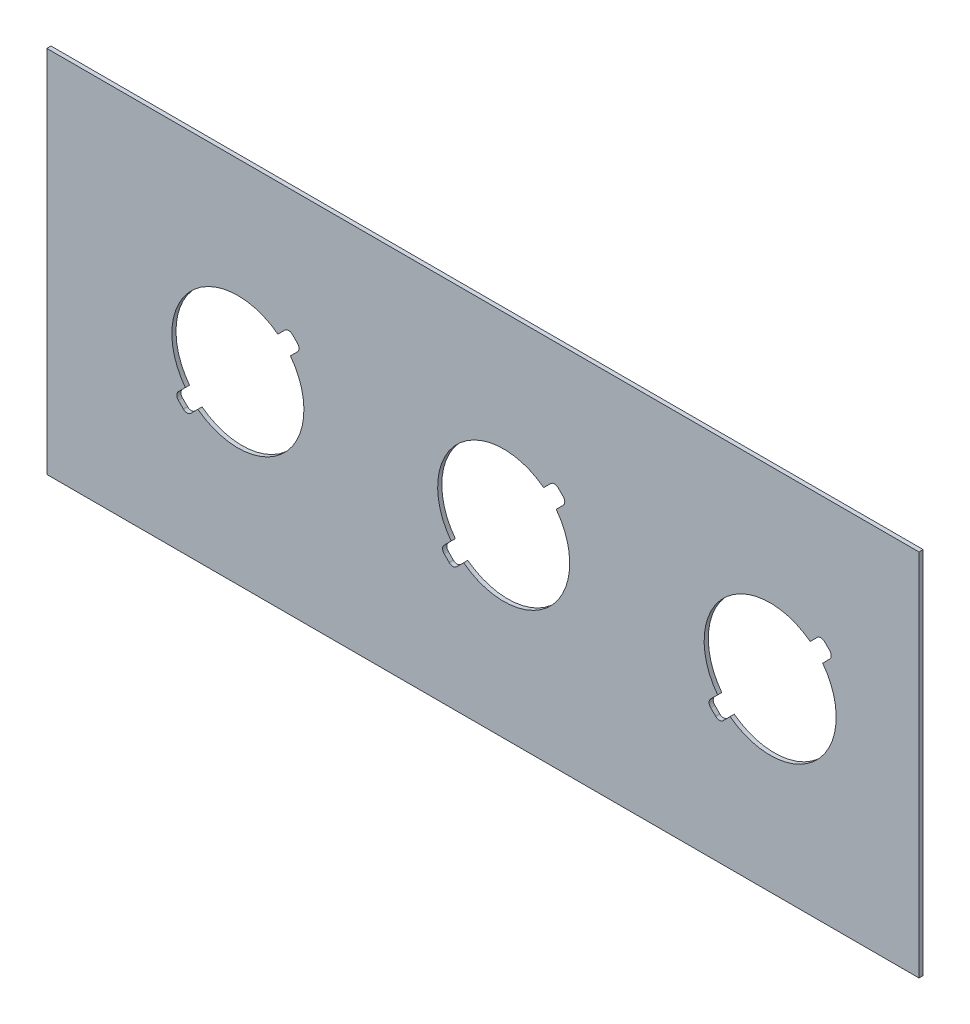
SolidWorks part; units mm, degrees
ref_plane "Front Plane" through (0, 0, 0) normal (0, 0, 1) x (1, 0, 0)
ref_plane "Top Plane" through (0, 0, 0) normal (0, 1, 0) x (1, 0, 0)
ref_plane "Right Plane" through (0, 0, 0) normal (1, 0, 0) x (0, 0, -1)
sketch "Sketch1" plane through (0, 0, 0) normal (0, 0, 1) x (1, 0, 0)
  line L1 (-165.1, -69.85) -> (165.1, -69.85)
  line L2 (-165.1, -69.85) -> (-165.1, 69.85)
  line L3 (-165.1, 69.85) -> (165.1, 69.85)
  line L4 (165.1, -69.85) -> (165.1, 69.85)
  line L5 (-165.1, -69.85) -> (165.1, 69.85) construction
  line L6 (-165.1, 69.85) -> (165.1, -69.85) construction
  point P0 (0, 0)
  dimension "D1" = 330.2
  dimension "D2" = 139.7
extrude "Boss-Extrude1" add sketch "Sketch1" along normal blind 1.5748
sketch "Sketch6" plane through (0, 0, 1.5748) normal (0, 0, 1) x (1, 0, 0)
  circle A10 centre (108.75, 0) radius 25
  circle A11 centre (7.861, 0) radius 25
  circle A12 centre (-92.774, 0) radius 25
  dimension "D1" = 50
extrude "Cut-Extrude3" cut sketch "Sketch6" against normal through all
sketch "Sketch8" plane through (0, 0, 1.5748) normal (0, 0, 1) x (1, 0, 0)
  line L0 (88.1205, -22.5387) -> (86.2113, -20.6295) construction
  line L1 (93.6006, -19.887) -> (90.9489, -22.5387) construction
  line L2 (86.2113, -17.8011) -> (88.863, -15.1494) construction
  line L3 (88.1205, -22.5387) -> (86.2113, -20.6295)
  line L4 (93.6006, -19.887) -> (90.9489, -22.5387)
  line L5 (86.2113, -17.8011) -> (88.863, -15.1494)
  line L6 (123.8994, 19.887) -> (126.5511, 22.5387) construction
  line L7 (131.2887, 17.8011) -> (128.637, 15.1494) construction
  line L8 (129.3795, 22.5387) -> (131.2887, 20.6295) construction
  line L9 (131.2887, 17.8011) -> (128.637, 15.1494)
  line L10 (129.3795, 22.5387) -> (131.2887, 20.6295)
  line L11 (123.8994, 19.887) -> (126.5511, 22.5387)
  line L12 (30.3997, 17.8011) -> (27.748, 15.1494) construction
  line L13 (28.4905, 22.5387) -> (30.3997, 20.6295) construction
  line L14 (23.0104, 19.887) -> (25.6621, 22.5387) construction
  line L15 (-7.2884, -19.887) -> (-9.9401, -22.5387) construction
  line L16 (-12.7685, -22.5387) -> (-14.6777, -20.6295) construction
  line L17 (-14.6777, -17.8011) -> (-12.026, -15.1494) construction
  line L18 (30.3997, 17.8011) -> (27.748, 15.1494)
  line L19 (28.4905, 22.5387) -> (30.3997, 20.6295)
  line L20 (23.0104, 19.887) -> (25.6621, 22.5387)
  line L21 (-7.2884, -19.887) -> (-9.9401, -22.5387)
  line L22 (-12.7685, -22.5387) -> (-14.6777, -20.6295)
  line L23 (-14.6777, -17.8011) -> (-12.026, -15.1494)
  line L24 (-115.3127, -17.8011) -> (-112.661, -15.1494) construction
  line L25 (-107.9234, -19.887) -> (-110.5751, -22.5387) construction
  line L26 (-113.4035, -22.5387) -> (-115.3127, -20.6295) construction
  line L27 (-115.3127, -17.8011) -> (-112.661, -15.1494)
  line L28 (-107.9234, -19.887) -> (-110.5751, -22.5387)
  line L29 (-113.4035, -22.5387) -> (-115.3127, -20.6295)
  line L30 (-70.2353, 17.8011) -> (-72.887, 15.1494) construction
  line L31 (-72.1445, 22.5387) -> (-70.2353, 20.6295) construction
  line L32 (-77.6246, 19.887) -> (-74.9729, 22.5387) construction
  line L33 (-70.2353, 17.8011) -> (-72.887, 15.1494)
  line L34 (-72.1445, 22.5387) -> (-70.2353, 20.6295)
  line L35 (-77.6246, 19.887) -> (-74.9729, 22.5387)
  arc A0 (86.2113, -17.8011) -> (86.2113, -20.6295) centre (87.6255, -19.2153) ccw construction
  arc A1 (88.1205, -22.5387) -> (90.9489, -22.5387) centre (89.5347, -21.1245) ccw construction
  arc A2 (131.2887, 17.8011) -> (131.2887, 20.6295) centre (129.8745, 19.2153) ccw construction
  arc A3 (86.2113, -17.8011) -> (86.2113, -20.6295) centre (87.6255, -19.2153) ccw
  arc A4 (88.1205, -22.5387) -> (90.9489, -22.5387) centre (89.5347, -21.1245) ccw
  arc A6 (129.3795, 22.5387) -> (126.5511, 22.5387) centre (127.9653, 21.1245) ccw construction
  arc A7 (131.2887, 17.8011) -> (131.2887, 20.6295) centre (129.8745, 19.2153) ccw
  arc A8 (129.3795, 22.5387) -> (126.5511, 22.5387) centre (127.9653, 21.1245) ccw
  arc A9 (30.3997, 17.8011) -> (30.3997, 20.6295) centre (28.9855, 19.2153) ccw construction
  arc A10 (28.4905, 22.5387) -> (25.6621, 22.5387) centre (27.0763, 21.1245) ccw construction
  arc A11 (-12.7685, -22.5387) -> (-9.9401, -22.5387) centre (-11.3543, -21.1245) ccw construction
  arc A12 (-14.6777, -17.8011) -> (-14.6777, -20.6295) centre (-13.2635, -19.2153) ccw construction
  arc A13 (30.3997, 17.8011) -> (30.3997, 20.6295) centre (28.9855, 19.2153) ccw
  arc A14 (28.4905, 22.5387) -> (25.6621, 22.5387) centre (27.0763, 21.1245) ccw
  arc A15 (-12.7685, -22.5387) -> (-9.9401, -22.5387) centre (-11.3543, -21.1245) ccw
  arc A16 (-14.6777, -17.8011) -> (-14.6777, -20.6295) centre (-13.2635, -19.2153) ccw
  arc A17 (-115.3127, -17.8011) -> (-115.3127, -20.6295) centre (-113.8985, -19.2153) ccw construction
  arc A18 (-113.4035, -22.5387) -> (-110.5751, -22.5387) centre (-111.9893, -21.1245) ccw construction
  arc A19 (-115.3127, -17.8011) -> (-115.3127, -20.6295) centre (-113.8985, -19.2153) ccw
  arc A20 (-113.4035, -22.5387) -> (-110.5751, -22.5387) centre (-111.9893, -21.1245) ccw
  arc A21 (-70.2353, 17.8011) -> (-70.2353, 20.6295) centre (-71.6495, 19.2153) ccw construction
  arc A22 (-72.1445, 22.5387) -> (-74.9729, 22.5387) centre (-73.5587, 21.1245) ccw construction
  arc A23 (-70.2353, 17.8011) -> (-70.2353, 20.6295) centre (-71.6495, 19.2153) ccw
  arc A24 (-72.1445, 22.5387) -> (-74.9729, 22.5387) centre (-73.5587, 21.1245) ccw
  arc A25 (128.637, 15.1494) -> (123.8994, 19.887) centre (108.75, 0) ccw
  arc A26 (27.748, 15.1494) -> (23.0104, 19.887) centre (7.861, 0) ccw
  arc A27 (-72.887, 15.1494) -> (-77.6246, 19.887) centre (-92.774, 0) ccw
  arc A28 (-112.661, -15.1494) -> (-107.9234, -19.887) centre (-92.774, 0) ccw
  arc A29 (-12.026, -15.1494) -> (-7.2884, -19.887) centre (7.861, 0) ccw
  arc A30 (88.863, -15.1494) -> (93.6006, -19.887) centre (108.75, 0) ccw
extrude "Cut-Extrude4" cut sketch "Sketch8" against normal blind 4
sketch "Sketch9" plane through (0, 0, 1.5748) normal (0, 0, 1) x (1, 0, 0)
  line L0 (108.75, -26.27) -> (108.75, -25)
  line L1 (135.02, -26.27) -> (82.48, -26.27) construction
  line L2 (82.48, 26.27) -> (135.02, 26.27) construction
  line L3 (135.02, 0) -> (133.75, 0)
  line L4 (82.48, -26.27) -> (82.48, 26.27) construction
  line L5 (-18.409, 0) -> (-17.139, 0)
  line L6 (34.131, 26.27) -> (34.131, -26.27) construction
  line L7 (-119.044, 0) -> (-117.774, 0)
  line L8 (-66.504, 26.27) -> (-66.504, -26.27) construction
  line L9 (7.861, 26.27) -> (7.861, 25)
  line L10 (34.131, -26.27) -> (-18.409, -26.27) construction
  line L11 (-92.774, 26.27) -> (-92.774, 25)
  line L12 (-66.504, -26.27) -> (-119.044, -26.27) construction
  line L16 (93.6006, -19.887) -> (90.9489, -22.5387) construction
  line L17 (88.1205, -22.5387) -> (86.2113, -20.6295) construction
  line L18 (86.2113, -17.8011) -> (88.863, -15.1494) construction
  line L19 (131.2887, 17.8011) -> (128.637, 15.1494) construction
  line L20 (129.3795, 22.5387) -> (131.2887, 20.6295) construction
  line L21 (123.8994, 19.887) -> (126.5511, 22.5387) construction
  line L22 (131.2887, 17.8011) -> (128.637, 15.1494)
  line L23 (129.3795, 22.5387) -> (131.2887, 20.6295)
  line L24 (123.8994, 19.887) -> (126.5511, 22.5387)
  line L25 (93.6006, -19.887) -> (90.9489, -22.5387)
  line L26 (88.1205, -22.5387) -> (86.2113, -20.6295)
  line L27 (86.2113, -17.8011) -> (88.863, -15.1494)
  line L28 (83.75, 0) -> (82.48, 0)
  line L29 (135.02, 26.27) -> (108.75, 26.27)
  line L30 (135.02, 26.27) -> (135.02, 0)
  line L31 (108.75, -26.27) -> (82.48, -26.27)
  line L32 (82.48, 0) -> (82.48, -26.27)
  line L34 (-7.2884, -19.887) -> (-9.9401, -22.5387) construction
  line L35 (-12.7685, -22.5387) -> (-14.6777, -20.6295) construction
  line L36 (108.75, 25) -> (108.75, 26.27)
  line L38 (-14.6777, -17.8011) -> (-12.026, -15.1494) construction
  line L39 (-7.2884, -19.887) -> (-9.9401, -22.5387)
  line L40 (-12.7685, -22.5387) -> (-14.6777, -20.6295)
  line L41 (-14.6777, -17.8011) -> (-12.026, -15.1494)
  line L42 (30.3997, 17.8011) -> (27.748, 15.1494) construction
  line L43 (28.4905, 22.5387) -> (30.3997, 20.6295) construction
  line L44 (23.0104, 19.887) -> (25.6621, 22.5387) construction
  line L45 (30.3997, 17.8011) -> (27.748, 15.1494)
  line L46 (28.4905, 22.5387) -> (30.3997, 20.6295)
  line L47 (23.0104, 19.887) -> (25.6621, 22.5387)
  line L48 (-107.9234, -19.887) -> (-110.5751, -22.5387) construction
  line L49 (-113.4035, -22.5387) -> (-115.3127, -20.6295) construction
  line L50 (-115.3127, -17.8011) -> (-112.661, -15.1494) construction
  line L51 (-107.9234, -19.887) -> (-110.5751, -22.5387)
  line L52 (-113.4035, -22.5387) -> (-115.3127, -20.6295)
  line L53 (-115.3127, -17.8011) -> (-112.661, -15.1494)
  line L54 (-77.6246, 19.887) -> (-74.9729, 22.5387) construction
  line L55 (-72.1445, 22.5387) -> (-70.2353, 20.6295) construction
  line L56 (-70.2353, 17.8011) -> (-72.887, 15.1494) construction
  line L57 (-77.6246, 19.887) -> (-74.9729, 22.5387)
  line L58 (-72.1445, 22.5387) -> (-70.2353, 20.6295)
  line L59 (-70.2353, 17.8011) -> (-72.887, 15.1494)
  line L60 (7.861, -25) -> (7.861, -26.27)
  line L61 (34.131, 26.27) -> (7.861, 26.27)
  line L62 (34.131, 26.27) -> (34.131, 0)
  line L63 (7.861, -26.27) -> (-18.409, -26.27)
  line L64 (-18.409, 0) -> (-18.409, -26.27)
  line L66 (-92.774, -25) -> (-92.774, -26.27)
  line L67 (-66.504, 26.27) -> (-92.774, 26.27)
  line L68 (-66.504, 26.27) -> (-66.504, 0)
  line L69 (-92.774, -26.27) -> (-119.044, -26.27)
  line L70 (-119.044, 0) -> (-119.044, -26.27)
  line L72 (-119.044, 26.27) -> (-66.504, 26.27) construction
  line L73 (32.861, 0) -> (34.131, 0)
  line L76 (-67.774, 0) -> (-66.504, 0)
  line L77 (-139.7, -69.85) -> (-139.7, 69.85)
  line L78 (-139.7, -88.9) -> (-139.7, 88.9) construction
  line L79 (-165.1, -69.85) -> (165.1, -69.85) construction
  line L80 (165.1, 69.85) -> (-165.1, 69.85) construction
  line L81 (-139.7, -49.75) -> (-165.1, -49.75)
  line L82 (-150.78, -49.75) -> (226.1, -49.75) construction
  line L83 (-165.1, 69.85) -> (-165.1, -69.85) construction
  line L84 (-139.7, 49.95) -> (-165.1, 49.95)
  line L85 (226.1, 49.95) -> (-150.78, 49.95) construction
  arc A0 (83.75, 0) -> (88.863, -15.1494) centre (108.75, 0) ccw
  arc A1 (32.861, 0) -> (27.748, 15.1494) centre (7.861, 0) ccw
  arc A2 (-67.774, 0) -> (-72.887, 15.1494) centre (-92.774, 0) ccw
  arc A3 (86.2113, -17.8011) -> (86.2113, -20.6295) centre (87.6255, -19.2153) ccw construction
  arc A5 (88.1205, -22.5387) -> (90.9489, -22.5387) centre (89.5347, -21.1245) ccw construction
  arc A6 (131.2887, 17.8011) -> (131.2887, 20.6295) centre (129.8745, 19.2153) ccw construction
  arc A7 (129.3795, 22.5387) -> (126.5511, 22.5387) centre (127.9653, 21.1245) ccw construction
  arc A8 (131.2887, 17.8011) -> (131.2887, 20.6295) centre (129.8745, 19.2153) ccw
  arc A9 (129.3795, 22.5387) -> (126.5511, 22.5387) centre (127.9653, 21.1245) ccw
  arc A10 (88.1205, -22.5387) -> (90.9489, -22.5387) centre (89.5347, -21.1245) ccw
  arc A11 (86.2113, -17.8011) -> (86.2113, -20.6295) centre (87.6255, -19.2153) ccw
  arc A12 (133.75, 0) -> (128.637, 15.1494) centre (108.75, 0) ccw
  arc A13 (93.6006, -19.887) -> (108.75, -25) centre (108.75, 0) ccw
  arc A14 (123.8994, 19.887) -> (108.75, 25) centre (108.75, 0) ccw
  arc A15 (-12.7685, -22.5387) -> (-9.9401, -22.5387) centre (-11.3543, -21.1245) ccw construction
  arc A16 (-14.6777, -17.8011) -> (-14.6777, -20.6295) centre (-13.2635, -19.2153) ccw construction
  arc A17 (-12.7685, -22.5387) -> (-9.9401, -22.5387) centre (-11.3543, -21.1245) ccw
  arc A18 (-14.6777, -17.8011) -> (-14.6777, -20.6295) centre (-13.2635, -19.2153) ccw
  arc A19 (30.3997, 17.8011) -> (30.3997, 20.6295) centre (28.9855, 19.2153) ccw construction
  arc A20 (28.4905, 22.5387) -> (25.6621, 22.5387) centre (27.0763, 21.1245) ccw construction
  arc A21 (30.3997, 17.8011) -> (30.3997, 20.6295) centre (28.9855, 19.2153) ccw
  arc A22 (28.4905, 22.5387) -> (25.6621, 22.5387) centre (27.0763, 21.1245) ccw
  arc A23 (-113.4035, -22.5387) -> (-110.5751, -22.5387) centre (-111.9893, -21.1245) ccw construction
  arc A24 (-115.3127, -17.8011) -> (-115.3127, -20.6295) centre (-113.8985, -19.2153) ccw construction
  arc A25 (-113.4035, -22.5387) -> (-110.5751, -22.5387) centre (-111.9893, -21.1245) ccw
  arc A26 (-115.3127, -17.8011) -> (-115.3127, -20.6295) centre (-113.8985, -19.2153) ccw
  arc A27 (-72.1445, 22.5387) -> (-74.9729, 22.5387) centre (-73.5587, 21.1245) ccw construction
  arc A28 (-70.2353, 17.8011) -> (-70.2353, 20.6295) centre (-71.6495, 19.2153) ccw construction
  arc A29 (-72.1445, 22.5387) -> (-74.9729, 22.5387) centre (-73.5587, 21.1245) ccw
  arc A30 (-70.2353, 17.8011) -> (-70.2353, 20.6295) centre (-71.6495, 19.2153) ccw
  arc A31 (-17.139, 0) -> (-12.026, -15.1494) centre (7.861, 0) ccw
  arc A32 (-7.2884, -19.887) -> (7.861, -25) centre (7.861, 0) ccw
  arc A33 (23.0104, 19.887) -> (7.861, 25) centre (7.861, 0) ccw
  arc A34 (-117.774, 0) -> (-112.661, -15.1494) centre (-92.774, 0) ccw
  arc A35 (-107.9234, -19.887) -> (-92.774, -25) centre (-92.774, 0) ccw
  arc A36 (-77.6246, 19.887) -> (-92.774, 25) centre (-92.774, 0) ccw
  point P20 (108.75, 0)
  point P24 (7.861, 0)
  point P29 (-92.774, 0)
  point P34 (7.861, 0)
  point P39 (-92.774, 0)
